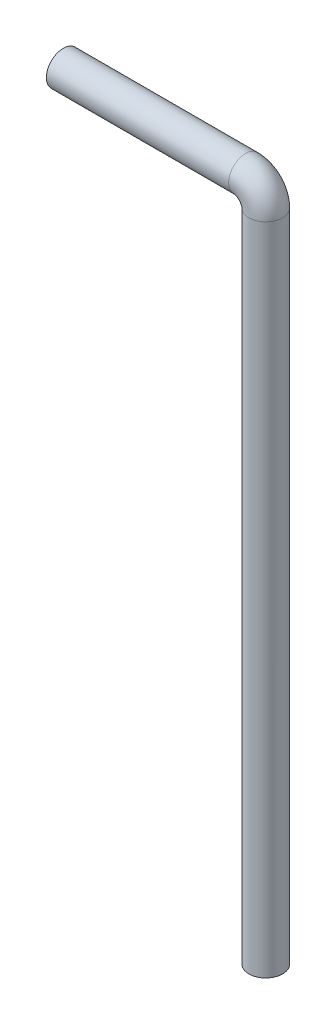
SolidWorks part; units mm, degrees
ref_plane "前基準面" through (0, 0, 0) normal (0, 0, 1) x (1, 0, 0)
ref_plane "上基準面" through (0, 0, 0) normal (0, 1, 0) x (1, 0, 0)
ref_plane "右基準面" through (0, 0, 0) normal (1, 0, 0) x (0, 0, -1)
sketch "草圖1" plane through (0, 0, 0) normal (0, 0, 1) x (1, 0, 0)
  line L0 (0, 0) -> (270, 0)
  line L1 (300, -30) -> (300, -1000)
  arc A0 (300, -30) -> (270, 0) centre (270, -30) ccw
  point P6 (300, 0)
  dimension "D3" = 30
  dimension "D1" = 300
  dimension "D2" = 1000
sketch "草圖2" plane through (0, 0, 0) normal (1, 0, 0) x (0, 0, -1)
  circle A0 centre (0, 0) radius 25
  circle A1 centre (0, 0) radius 20.0522
  dimension "D1" = 50
sweep "掃出3" add profiles "草圖2" path "草圖1"
